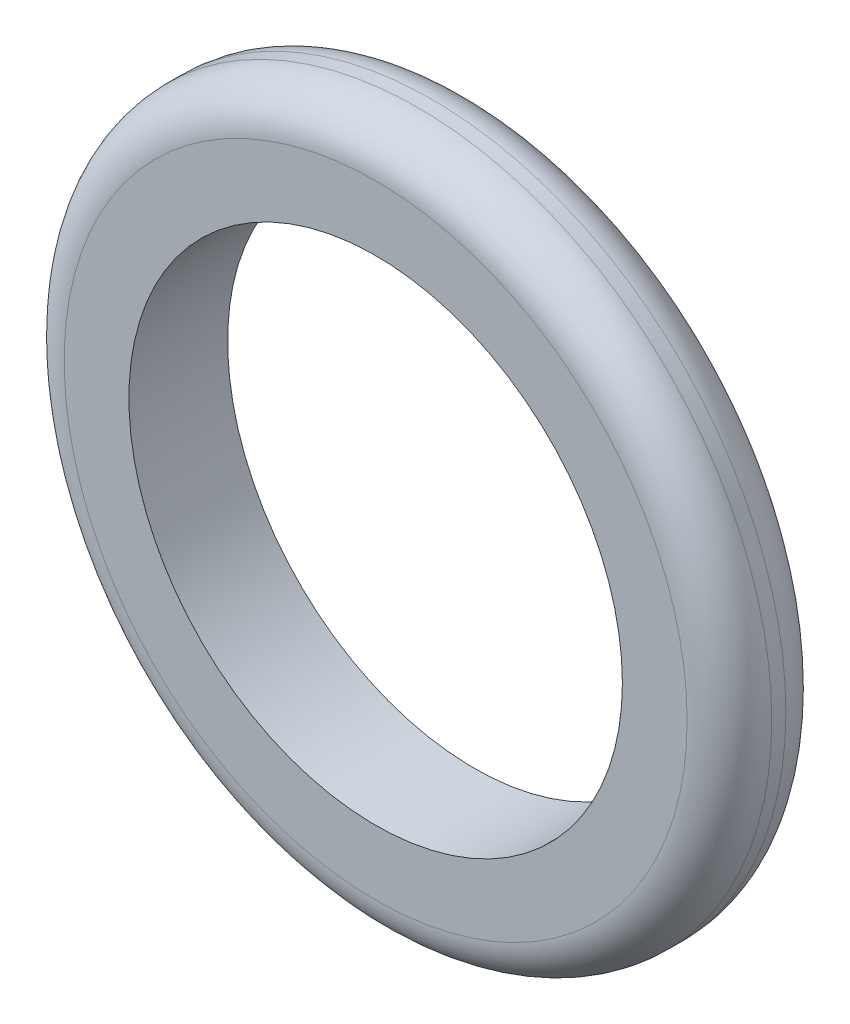
SolidWorks part; units mm, degrees
material "Rubber"
ref_plane "Front Plane" through (0, 0, 0) normal (0, 0, 1) x (1, 0, 0)
ref_plane "Top Plane" through (0, 0, 0) normal (0, 1, 0) x (1, 0, 0)
ref_plane "Right Plane" through (0, 0, 0) normal (1, 0, 0) x (0, 0, -1)
sketch "Sketch1" plane through (0, 0, 0) normal (0, 0, 1) x (1, 0, 0)
  circle A0 centre (0, -38.2966) radius 250.9326
extrude "Boss-Extrude1" add sketch "Sketch1" along normal mid plane 70
fillet "Fillet1" radius 30 2 edges at (250.9326, -38.2966, -35) (250.9326, -38.2966, 35)
sketch "Sketch2" plane through (0, 0, 35) normal (0, 0, 1) x (1, 0, 0)
  circle A0 centre (0, -38.2966) radius 175
  dimension "D1" = 350
extrude "Cut-Extrude1" cut sketch "Sketch2" against normal blind 70
